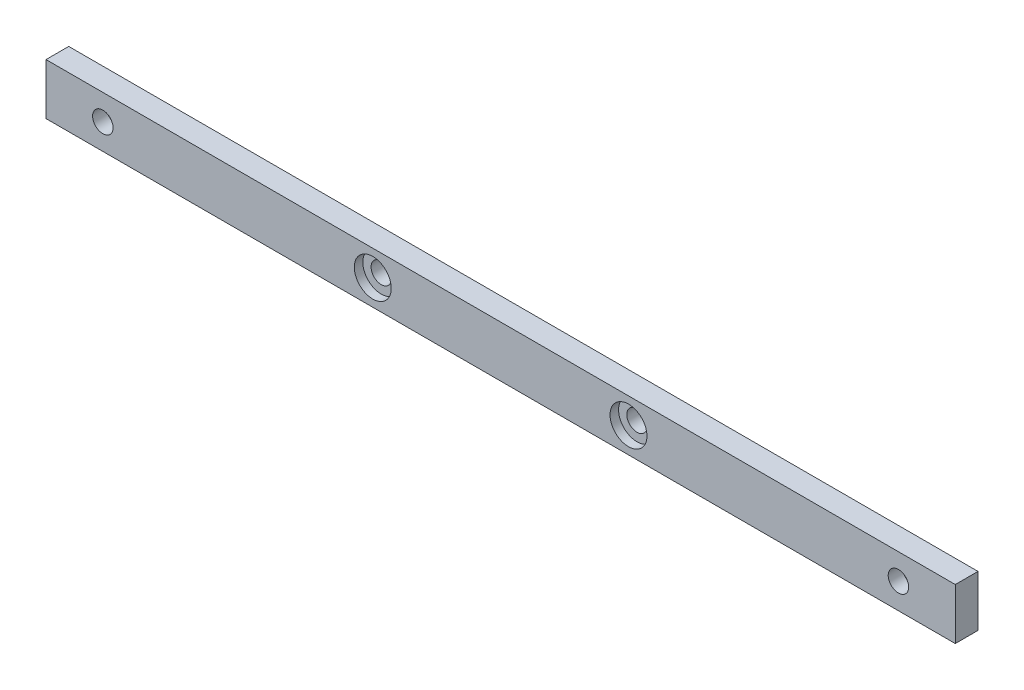
SolidWorks part; units mm, degrees
ref_plane "前视基准面" through (0, 0, 0) normal (0, 0, 1) x (1, 0, 0)
ref_plane "上视基准面" through (0, 0, 0) normal (0, 1, 0) x (1, 0, 0)
ref_plane "右视基准面" through (0, 0, 0) normal (1, 0, 0) x (0, 0, -1)
other "Configuration Table"
sketch "草图1" plane through (0, 0, 0) normal (0, 0, 1) x (1, 0, 0)
  line L0 (0, 5) -> (60, 5) construction
  line L1 (0, 0) -> (60, 0)
  line L2 (0, 0) -> (0, 10)
  line L3 (0, 10) -> (60, 10)
  line L4 (60, 0) -> (60, 10)
  line L5 (30, 10) -> (30, 0) construction
  line L6 (7.5, 5) -> (52.5, 5) construction
  circle A0 centre (7.5, 5) radius 1.8
  circle A1 centre (52.5, 5) radius 1.8
  point P11 (30, 5)
  point P12 (30, 5)
  dimension "D3" = 3.6
  dimension "D4" = 3.6
  dimension "D1" = 60
  dimension "D2" = 45
  dimension "D5" = 10
extrude "凸台-拉伸1" add sketch "草图1" along normal blind 4
sketch "草图2" plane through (0, 0, 4) normal (0, 0, 1) x (1, 0, 0)
  circle A0 centre (7.5, 5) radius 3
  circle A1 centre (52.5, 5) radius 3
  dimension "D1" = 6
  dimension "D2" = 6
extrude "切除-拉伸1" cut sketch "草图2" against normal blind 2
sketch "草图3" plane through (0, 0, 4) normal (0, 0, 1) x (1, 0, 0)
  line L0 (0, 0) -> (0, -4)
  line L1 (0, -4) -> (60, -4)
  line L2 (60, -4) -> (60, 0)
  line L3 (60, 0) -> (0, 0)
  dimension "D1" = 4
extrude "凸台-拉伸2" [suppressed] add sketch "草图3" along normal blind 30 and the other way up to surface
sketch "草图4" [suppressed] plane through (0, 0, 0) normal (0, 1, 0) x (1, 0, 0)
  line L0 (0, -19) -> (60, -19) construction
  line L1 (7.5, -19) -> (52.5, -19) construction
  line L4 (60, -4) -> (0, -4)
  line L5 (0, -4) -> (0, -34)
  line L6 (0, -34) -> (60, -34)
  line L7 (60, -34) -> (60, -4)
  line L8 (60, -4) -> (0, -4) construction
  line L9 (0, -4) -> (0, -34) construction
  line L10 (0, -34) -> (60, -34) construction
  line L11 (60, -34) -> (60, -4) construction
  circle A0 centre (7.5, -19) radius 1.8
  circle A1 centre (52.5, -19) radius 1.8
  point P6 (30, -19)
  point P9 (30, -19)
  dimension "D3" = 3.6
  dimension "D4" = 3.6
  dimension "D2" = 45
  dimension "D1" = 0
extrude "切除-拉伸2" [suppressed] cut sketch "草图4" against normal up to next
sketch "草图5" [suppressed] plane through (0, 0, 0) normal (0, 1, 0) x (1, 0, 0)
  circle A0 centre (7.5, -19) radius 3
  circle A1 centre (52.5, -19) radius 3
  dimension "D1" = 6
  dimension "D2" = 6
extrude "切除-拉伸3" [suppressed] cut sketch "草图5" against normal blind 1.5
sketch "草图6" plane through (0, 0, 4) normal (0, 0, 1) x (1, 0, 0)
  line L0 (-50, 10) -> (110, 10)
  line L1 (-50, 10) -> (-50, 19)
  line L2 (-50, 19) -> (110, 19)
  line L3 (110, 19) -> (110, 10)
  line L4 (0, 10) -> (0, 0)
  line L5 (0, 0) -> (60, 0)
  line L6 (60, 0) -> (60, 10)
  line L7 (60, 10) -> (0, 10)
  line L8 (0, 10) -> (0, 0) construction
  line L10 (60, 0) -> (60, 10) construction
  line L11 (60, 10) -> (0, 10) construction
  line L12 (-50, 14.5) -> (110, 14.5) construction
  line L13 (30, 10) -> (30, 50010) construction
  line L14 (-40, 14.5) -> (100, 14.5)
  line L19 (0, 0) -> (60, 0)
  point P6 (30, 10)
  point P7 (30, 10)
  point P16 (30, 14.5)
  point P17 (30, 14.5)
  dimension "D2" = 160
  dimension "D3" = 9
  dimension "D4" = 140
  dimension "D1" = 0
extrude "凸台-拉伸3" add sketch "草图6" against normal up to surface (4 mm away) contours L3 L0 L1 L2 up to face at (9.3, 5, 0)
sketch "草图7" plane through (0, 0, 4) normal (0, 0, 1) x (1, 0, 0)
  line L0 (-50, 14.5) -> (110, 14.5) construction
  line L1 (-40, 14.5) -> (100, 14.5) construction
  line L8 (0, 10) -> (0, 0)
  line L9 (0, 0) -> (60, 0)
  line L10 (60, 0) -> (60, 10)
  line L11 (60, 10) -> (110, 10)
  line L12 (110, 10) -> (110, 19)
  line L13 (110, 19) -> (-50, 19)
  line L14 (-50, 19) -> (-50, 10)
  line L15 (-50, 10) -> (0, 10)
  line L16 (0, 10) -> (0, 0) construction
  line L18 (60, 0) -> (60, 10) construction
  line L19 (60, 10) -> (110, 10) construction
  line L20 (110, 10) -> (110, 19) construction
  line L21 (110, 19) -> (-50, 19) construction
  line L22 (-50, 19) -> (-50, 10) construction
  line L23 (-50, 10) -> (0, 10) construction
  line L26 (0, 0) -> (60, 0)
  circle A0 centre (-40, 14.5) radius 1.8
  circle A1 centre (100, 14.5) radius 1.8
  point P6 (30, 14.5)
  point P12 (30, 14.5)
  dimension "D3" = 3.6
  dimension "D4" = 3.6
  dimension "D2" = 140
  dimension "D1" = 0
extrude "切除-拉伸4" cut sketch "草图7" against normal up to surface (4 mm away) contours A1 | A0 up to face at (9.3, 5, 0)
fillet "圆角1" [suppressed] radius 1
sketch "草图8" plane through (0, 0, 0) normal (0, 0, -1) x (-1, 0, 0)
  circle A0 centre (-100, 14.5) radius 3.25
  circle A1 centre (40, 14.5) radius 3.25
  dimension "D1" = 6.5
  dimension "D2" = 6.5
extrude "切除-拉伸5" cut sketch "草图8" against normal blind 1.5
sketch "草图9" plane through (0, 0, 4) normal (0, 0, 1) x (1, 0, 0)
  line L0 (30, 19) -> (30, -49981) construction
  line L1 (-50, 19) -> (110, 19) construction
  line L2 (-50, 14.5) -> (49950, 14.5) construction
  line L3 (-50, 10) -> (-50, 19) construction
  line L4 (7.5, 14.5) -> (52.5, 14.5) construction
  circle A0 centre (7.5, 14.5) radius 1.8
  circle A1 centre (52.5, 14.5) radius 1.8
  point P4 (30, 19)
  point P9 (-50, 14.5)
  point P10 (30, 14.5)
  point P13 (30, 14.5)
  dimension "D2" = 3.6
  dimension "D3" = 3.6
  dimension "D1" = 45
extrude "切除-拉伸6" cut sketch "草图9" against normal up to next
sketch "草图10" plane through (0, 0, 4) normal (0, 0, 1) x (1, 0, 0)
  line L0 (0, 10) -> (60, 10)
  line L8 (0, 10) -> (0, 0)
  line L9 (0, 0) -> (60, 0)
  line L10 (60, 0) -> (60, 10)
  line L11 (60, 10) -> (110, 10)
  line L12 (110, 10) -> (110, 19)
  line L13 (110, 19) -> (-50, 19)
  line L14 (-50, 19) -> (-50, 10)
  line L15 (-50, 10) -> (0, 10)
  line L16 (0, 10) -> (0, 0)
  line L17 (0, 0) -> (60, 0)
  line L18 (60, 0) -> (60, 10)
  dimension "D1" = 0
extrude "切除-拉伸7" cut sketch "草图10" against normal up to next
sketch "草图11" plane through (0, 0, 4) normal (0, 0, 1) x (1, 0, 0)
  circle A0 centre (7.5, 14.5) radius 3.25
  circle A1 centre (52.5, 14.5) radius 3.25
  dimension "D1" = 6.5
  dimension "D2" = 6.5
extrude "切除-拉伸8" cut sketch "草图11" against normal blind 1.5
